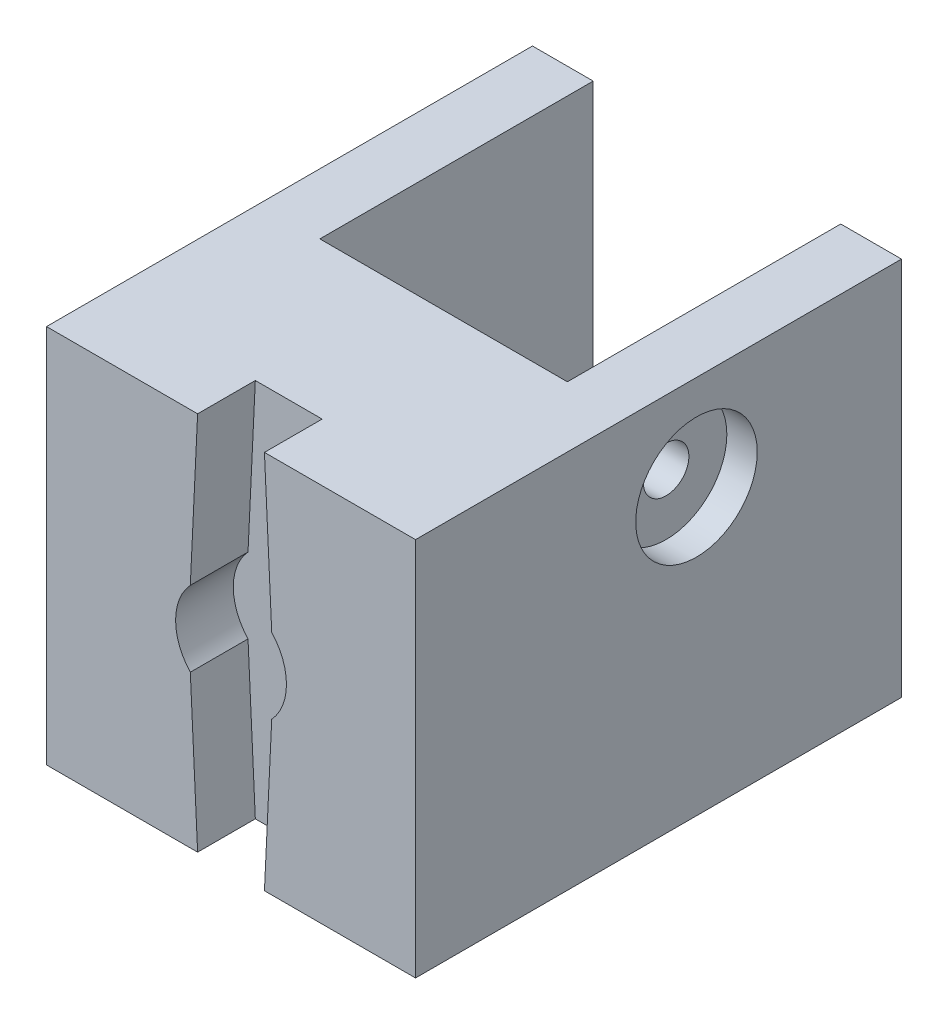
SolidWorks part; units mm, degrees
ref_plane "Front Plane" through (0, 0, 0) normal (0, 0, 1) x (1, 0, 0)
ref_plane "Top Plane" through (0, 0, 0) normal (0, 1, 0) x (1, 0, 0)
ref_plane "Right Plane" through (0, 0, 0) normal (1, 0, 0) x (0, 0, -1)
sketch "Sketch1" plane through (0, 0, 0) normal (0, 1, 0) x (1, 0, 0)
  line L0 (-8.15, 18) -> (-8.15, 0)
  line L1 (-8.15, 0) -> (8.15, 0)
  line L2 (8.15, 0) -> (8.15, 18)
  point P3 (0, 0)
  dimension "D1" = 16.3
  dimension "D2" = 18
extrude "Extrude-Thin1" add sketch "Sketch1" along normal blind 25 thin
sketch "Sketch2" plane through (0, 0, 4) normal (0, 0, 1) x (1, 0, 0)
  line L4 (-12.15, 0) -> (12.15, 0)
  line L5 (12.15, 0) -> (12.15, 25)
  line L6 (12.15, 25) -> (-12.15, 25)
  line L7 (-12.15, 25) -> (-12.15, 0)
  line L8 (-12.15, 0) -> (12.15, 0)
  line L9 (12.15, 0) -> (12.15, 25)
  line L10 (12.15, 25) -> (-12.15, 25)
  line L11 (-12.15, 25) -> (-12.15, 0)
  dimension "D1" = 0
extrude "Boss-Extrude1" add sketch "Sketch2" along normal blind 10
sketch "Sketch3" plane through (0, 0, 14) normal (0, 0, 1) x (1, 0, 0)
  line L0 (0, 25) -> (0, 0) construction
  line L1 (12.15, 25) -> (-12.15, 25) construction
  line L2 (-12.15, 0) -> (12.15, 0) construction
  line L3 (-2.2, 25) -> (-2.8, 12.5)
  line L4 (2.2, 25) -> (2.8, 12.5)
  line L5 (-12.15, 12.5) -> (12.15, 12.5) construction
  line L6 (-12.15, 25) -> (-12.15, 0) construction
  line L7 (12.15, 0) -> (12.15, 25) construction
  line L8 (2.2, 0) -> (2.8, 12.5)
  line L9 (-2.2, 0) -> (-2.8, 12.5)
  arc A0 (-2.2, 25) -> (2.2, 25) centre (0, 24.8944) cw
  arc A1 (-2.2, 0) -> (2.2, 0) centre (0, 0.1056) ccw
  point P8 (0, 12.5)
  dimension "D1" = 2.2
  dimension "D2" = 2.8
extrude "Cut-Extrude1" cut sketch "Sketch3" against normal blind 3.8
sketch "Sketch4" plane through (0, 0, 14) normal (0, 0, 1) x (1, 0, 0)
  line L0 (0, 25) -> (0, 0) construction
  line L1 (-2.2, 25) -> (2.2, 25) construction
  line L2 (-2.2, 0) -> (2.2, 0) construction
  circle A0 centre (0, 12.5) radius 3.65
  dimension "D1" = 7.3
extrude "Cut-Extrude2" cut sketch "Sketch4" against normal blind 3.8
sketch "Sketch5" plane through (8.15, 0, 0) normal (-1, 0, 0) x (0, 0, 1)
  line L0 (-9, 25) -> (-9, 0) construction
  line L1 (0, 25) -> (-18, 25) construction
  line L2 (0, 0) -> (-18, 0) construction
  line L3 (-18, 12.5) -> (0, 12.5) construction
  line L4 (-18, 25) -> (-18, 0) construction
  line L5 (0, 25) -> (0, 0) construction
  line L7 (-4.5, 18.75) -> (-9, 12.5) construction
  circle A0 centre (-4.5, 18.75) radius 1.5
  point P6 (0, 0)
  point P14 (-4.6236, 18.5784)
  point P19 (0, 0)
  point P21 (0, 0)
  dimension "D1" = 3
  dimension "D2" = 4.5
  dimension "D3" = 6.25
extrude "Cut-Extrude3" cut sketch "Sketch5" against normal through all
sketch "Sketch7" plane through (-8.15, 0, 0) normal (1, 0, 0) x (0, 0, -1)
  line L0 (9, 25) -> (9, 0) construction
  line L1 (18, 25) -> (0, 25) construction
  line L2 (18, 0) -> (0, 0) construction
  line L3 (18, 12.5) -> (0, 12.5) construction
  line L4 (18, 25) -> (18, 0) construction
  line L5 (0, 25) -> (0, 0) construction
  line L7 (18, 0) -> (13.5, 6.25) construction
  line L8 (13.5, 6.25) -> (9, 12.5) construction
  circle A0 centre (13.5, 6.25) radius 1.5
  dimension "D1" = 3
  dimension "D2" = 6.25
extrude "Cut-Extrude4" cut sketch "Sketch7" against normal through all
sketch "Sketch8" plane through (12.15, 0, 0) normal (1, 0, 0) x (0, 0, -1)
  circle A0 centre (4.5, 18.75) radius 4
  dimension "D1" = 8
extrude "Cut-Extrude5" cut sketch "Sketch8" against normal blind 2
sketch "Sketch9" plane through (-12.15, 0, 0) normal (-1, 0, 0) x (0, 0, 1)
  circle A0 centre (-13.5, 6.25) radius 4
  dimension "D1" = 8
extrude "Cut-Extrude6" cut sketch "Sketch9" against normal blind 2
